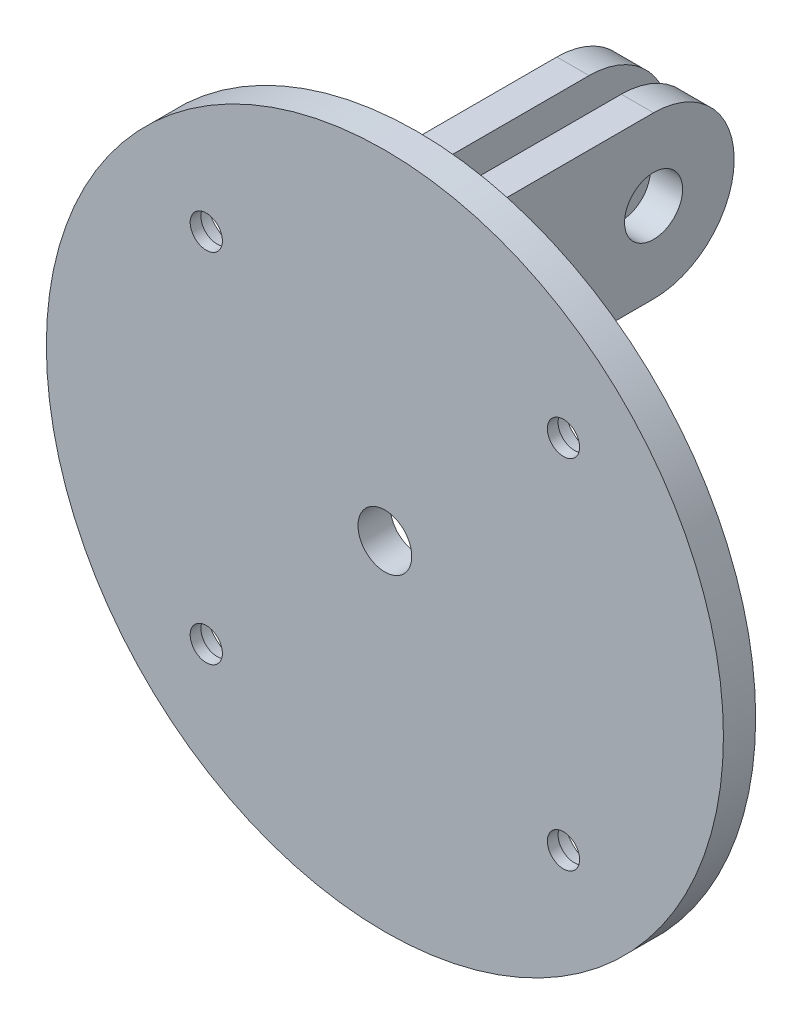
SolidWorks part; units mm, degrees
ref_plane "Alzado" through (0, 0, 0) normal (0, 0, 1) x (1, 0, 0)
ref_plane "Planta" through (0, 0, 0) normal (0, 1, 0) x (1, 0, 0)
ref_plane "Vista lateral" through (0, 0, 0) normal (1, 0, 0) x (0, 0, -1)
sketch "Croquis1" plane through (0, 0, 0) normal (0, 0, 1) x (1, 0, 0)
  line L1 (-21.1753, 30.481) -> (-65.7231, 30.481) construction
  line L3 (-65.7231, -14.0668) -> (-21.1753, -14.0668) construction
  line L4 (-21.1753, -14.0668) -> (-21.1753, 30.481) construction
  line L5 (-21.1753, 30.481) -> (-65.7231, -14.0668) construction
  line L6 (-65.7231, -14.0668) -> (-65.7231, 30.481) construction
  line L7 (-65.7231, 30.481) -> (-21.1753, -14.0668) construction
  circle A0 centre (-43.4492, 8.2071) radius 31.5
  circle A2 centre (-60.0662, 24.8241) radius 1.5
  circle A3 centre (-26.8322, 24.8241) radius 1.5
  circle A4 centre (-26.8322, -8.4099) radius 1.5
  circle A5 centre (-60.0662, -8.4099) radius 1.5
  dimension "D1" = 63
  dimension "D3" = 8
  dimension "D4" = 8
  dimension "D5" = 8
  dimension "D6" = 8
extrude "Saliente-Extruir1" add sketch "Croquis1" along normal blind 3
sketch "Croquis4" plane through (0, 0, 0) normal (0, 0, -1) x (-1, 0, 0)
  circle A0 centre (43.4492, 8.2071) radius 2.5
  dimension "D1" = 5
extrude "Cortar-Extruir3" cut sketch "Croquis4" against normal blind 3
sketch "Croquis5" plane through (0, 0, 0) normal (0, 0, -1) x (-1, 0, 0)
  line L0 (43.4492, 8.2071) -> (43.4492, 39.7071) construction
  line L1 (43.4492, 34.7071) -> (47.9492, 34.7071) construction
  line L2 (47.9492, 34.7071) -> (47.9492, 19.7071) construction
  line L3 (41.9492, 19.7071) -> (41.9492, 34.7071)
  line L5 (47.9492, 34.7071) -> (47.9492, 19.7071)
  line L7 (38.9492, 34.7071) -> (38.9492, 19.7071)
  line L8 (44.9492, 19.7071) -> (44.9492, 34.7071)
  line L9 (44.9492, 19.7071) -> (47.9492, 19.7071)
  line L10 (38.9492, 19.7071) -> (41.9492, 19.7071)
  line L11 (38.9492, 34.7071) -> (41.9492, 34.7071)
  line L12 (44.9492, 34.7071) -> (47.9492, 34.7071)
  circle A0 centre (43.4492, 8.2071) radius 31.5 construction
  dimension "D1" = 5
  dimension "D2" = 4.5
  dimension "D3" = 15
  dimension "D4" = 9
  dimension "D5" = 3
  dimension "D6" = 3
extrude "Saliente-Extruir2" add sketch "Croquis5" along normal blind 25
sketch "Croquis6" plane through (-38.9492, 0, 0) normal (1, 0, 0) x (0, 0, -1)
  line L0 (25, 34.7071) -> (17.5, 34.7071) construction
  line L1 (25, 34.7071) -> (0, 34.7071) construction
  line L2 (17.5, 34.7071) -> (17.5, 27.2071) construction
  line L3 (17.5, 27.2071) -> (17.5, 19.7071) construction
  line L4 (25, 19.7071) -> (0, 19.7071) construction
  line L5 (17.5, 34.7071) -> (25, 34.7071)
  line L6 (25, 34.7071) -> (25, 19.7071)
  line L7 (25, 19.7071) -> (17.5, 19.7071)
  arc A0 (17.5, 34.7071) -> (17.5, 19.7071) centre (17.5, 27.2071) cw
  circle A1 centre (17.5, 27.2071) radius 2.7
  line M2 (0, 19.7071) -> (25, 19.7071)
  line M3 (25, 19.7071) -> (25, 34.7071)
  line M4 (25, 34.7071) -> (0, 34.7071)
  dimension "D1" = 5.4
extrude "Cortar-Extruir4" cut sketch "Croquis6" against normal up to vertex contours A0 L6 M4 | A0 M3 M2 | A1
sketch "Croquis7" plane through (0, 0, 0) normal (0, 0, -1) x (-1, 0, 0)
  circle A0 centre (26.8322, 24.8241) radius 3
  circle A1 centre (60.0662, 24.8241) radius 3
  circle A2 centre (60.0662, -8.4099) radius 3
  circle A3 centre (26.8322, -8.4099) radius 3
extrude "Cortar-Extruir5" cut sketch "Croquis7" against normal blind 2
